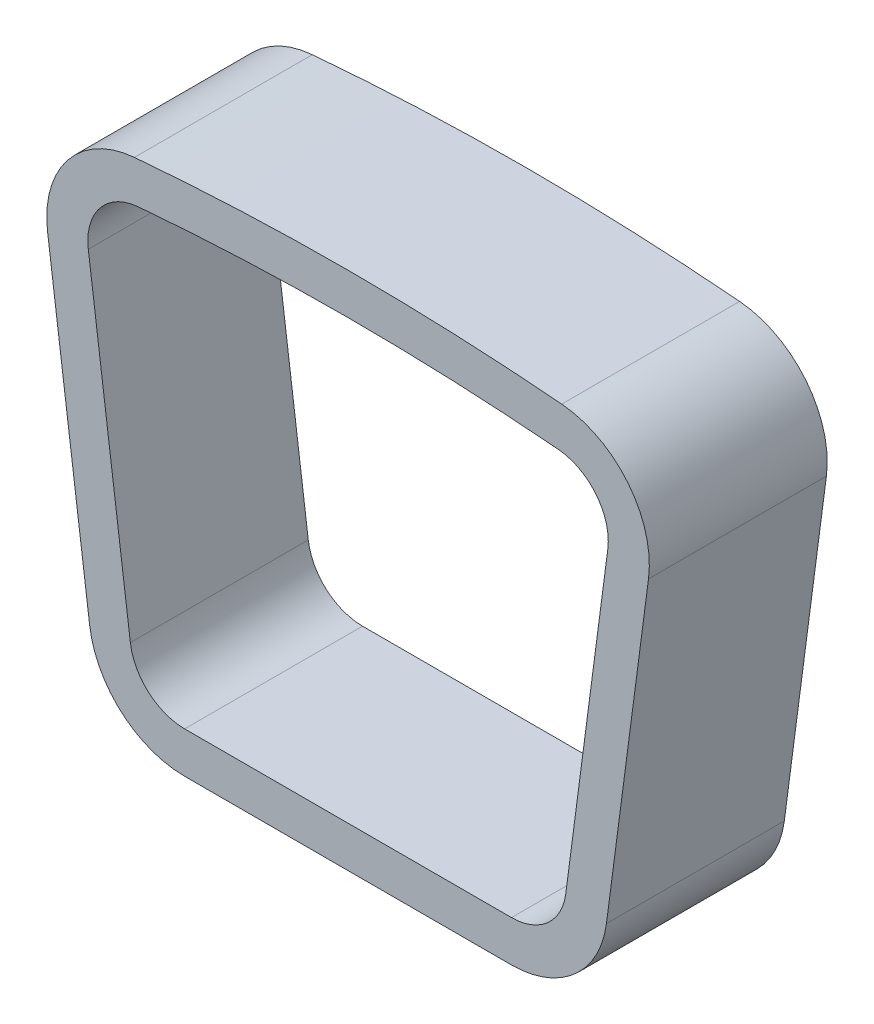
SolidWorks part; units mm, degrees
material "Copper"
ref_plane "Front Plane" through (0, 0, 0) normal (0, 0, 1) x (1, 0, 0)
ref_plane "Top Plane" through (0, 0, 0) normal (0, 1, 0) x (1, 0, 0)
ref_plane "Right Plane" through (0, 0, 0) normal (1, 0, 0) x (0, 0, -1)
sketch "Sketch1" plane through (0, 0, 0) normal (0, 0, 1) x (1, 0, 0)
  line L1 (9.4411, 75.5432) -> (10.9787, 87.2222)
  line L2 (-10.9787, 87.2222) -> (-9.4411, 75.5432)
  line L3 (-5.9711, 72.5) -> (5.9711, 72.5)
  line L4 (-9.4915, 87.418) -> (-7.954, 75.7389)
  line L5 (-5.9711, 74) -> (5.9711, 74)
  line L6 (7.954, 75.7389) -> (9.4915, 87.418)
  line L7 (-9.4915, 87.418) -> (-7.954, 75.7389)
  line L8 (-5.9711, 74) -> (5.9711, 74)
  line L9 (7.954, 75.7389) -> (9.4915, 87.418)
  arc A0 (10.9787, 87.2222) -> (7.8073, 91.1663) centre (7.5087, 87.6791) ccw
  arc A1 (7.8073, 91.1663) -> (-7.8073, 91.1663) centre (0, 0) ccw
  arc A2 (-7.8073, 91.1663) -> (-10.9787, 87.2222) centre (-7.5087, 87.6791) ccw
  arc A3 (-9.4411, 75.5432) -> (-5.9711, 72.5) centre (-5.9711, 76) ccw
  arc A4 (5.9711, 72.5) -> (9.4411, 75.5432) centre (5.9711, 76) ccw
  arc A5 (7.6793, 89.6718) -> (-7.6793, 89.6718) centre (0, 0) ccw
  arc A6 (-7.6793, 89.6718) -> (-9.4915, 87.418) centre (-7.5087, 87.6791) ccw
  arc A7 (-7.954, 75.7389) -> (-5.9711, 74) centre (-5.9711, 76) ccw
  arc A8 (5.9711, 74) -> (7.954, 75.7389) centre (5.9711, 76) ccw
  arc A9 (9.4915, 87.418) -> (7.6793, 89.6718) centre (7.5087, 87.6791) ccw
  arc A10 (7.6793, 89.6718) -> (-7.6793, 89.6718) centre (0, 0) ccw
  arc A11 (-7.6793, 89.6718) -> (-9.4915, 87.418) centre (-7.5087, 87.6791) ccw
  arc A12 (-7.954, 75.7389) -> (-5.9711, 74) centre (-5.9711, 76) ccw
  arc A13 (5.9711, 74) -> (7.954, 75.7389) centre (5.9711, 76) ccw
  arc A14 (9.4915, 87.418) -> (7.6793, 89.6718) centre (7.5087, 87.6791) ccw
  dimension "D1" = 0
  dimension "D2" = 1.5
extrude "Boss-Extrude1" add sketch "Sketch1" along normal up to surface (6.5 mm away)
